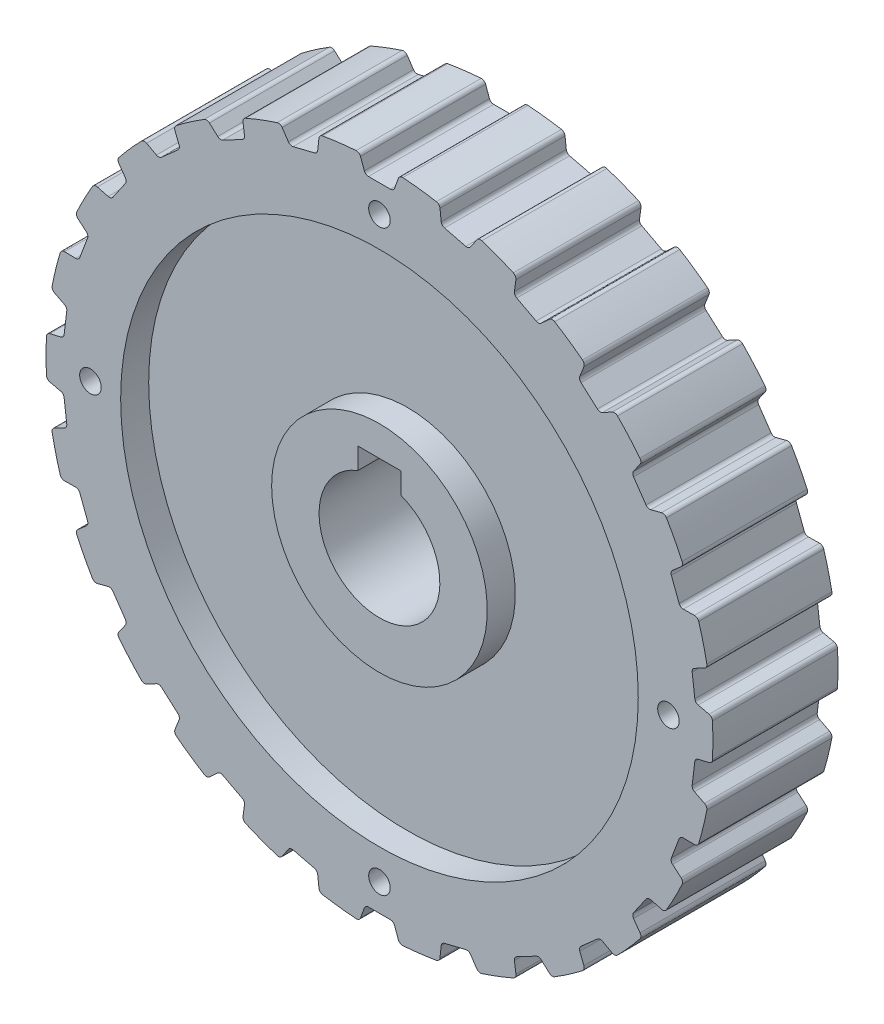
SolidWorks part; units mm, degrees
ref_plane "Front Plane" through (0, 0, 0) normal (0, 0, 1) x (1, 0, 0)
ref_plane "Top Plane" through (0, 0, 0) normal (0, 1, 0) x (1, 0, 0)
ref_plane "Right Plane" through (0, 0, 0) normal (1, 0, 0) x (0, 0, -1)
sketch "Sketch1" plane through (0, 0, 0) normal (0, 1, 0) x (1, 0, 0)
  line L0 (0, 36.1296) -> (0, -19.4741) construction
sketch "Sketch2" plane through (0, 0, 0) normal (0, 1, 0) x (1, 0, 0)
  line L0 (7, 7.25) -> (12.5, 7.25)
  line L1 (12.5, 7.25) -> (12.5, 4)
  line L2 (12.5, 4) -> (30, 4)
  line L3 (30, 4) -> (30, 7.25)
  line L4 (30, 7.25) -> (36, 7.25)
  line L5 (36, 7.25) -> (36, -7.25)
  line L6 (36, -7.25) -> (30, -7.25)
  line L7 (30, -7.25) -> (30, -4)
  line L8 (30, -4) -> (12.5, -4)
  line L9 (12.5, -4) -> (12.5, -7.25)
  line L10 (12.5, -7.25) -> (7, -7.25)
  line L11 (7, -7.25) -> (7, 7.25)
  line L12 (0, 0) -> (7, 0) construction
  line L13 (0, 200036.1296) -> (0, -200019.4741) construction
  dimension "D1" = 36
  dimension "D2" = 30
  dimension "D3" = 12.5
  dimension "D4" = 14.5
  dimension "D5" = 3.25
  dimension "D6" = 7
revolve "Revolve1" add sketch "Sketch2" angle 360 about L0
sketch "Sketch3" plane through (0, 0, 0) normal (0, 0, 1) x (1, 0, 0)
  line L0 (0, 0) -> (0, 9) construction
  line L1 (-2.5, 0) -> (2.5, 0)
  line L2 (-2.5, 0) -> (-2.5, 9)
  line L3 (-2.5, 9) -> (2.5, 9)
  line L4 (2.5, 0) -> (2.5, 9)
  line L5 (0, 9) -> (0, 12.5) construction
  circle A0 centre (0, 0) radius 12.5 construction
  dimension "D1" = 3.5
  dimension "D2" = 5
extrude "Cut-Extrude1" cut sketch "Sketch3" against normal through all both and the other way through all
sketch "Sketch4" plane through (0, 0, 0) normal (0, 0, 1) x (1, 0, 0)
  line L0 (0, 0) -> (0, 30) construction
  line L1 (0, 30) -> (0, 32) construction
  line L2 (0, 32) -> (0, 33.5) construction
  circle A0 centre (0, 0) radius 30 construction
  circle A1 centre (0, 33.5) radius 1.5 construction
  circle A2 centre (33.5, 0) radius 1.5 construction
  circle A3 centre (0, -33.5) radius 1.5 construction
  circle A4 centre (-33.5, 0) radius 1.5 construction
  point P18 (0, 0)
  dimension "D2" = 3
  dimension "D1" = 2
  dimension "D3" = 4
hole_wizard "M3x0.5 Tapped Hole1" positions "Sketch5" profile "Sketch6" tap size "M3x0.5" standard "ANSI Metric" end condition through all
sketch "Sketch5" plane through (0, 0, 7.25) normal (0, 0, 1) x (1, 0, 0)
  point P0 (0, 33.5)
  point P3 (33.5, 0)
  point P6 (-33.5, 0)
  point P9 (0, -33.5)
sketch "Sketch6" plane through (0, 33.5, 7.25) normal (1, 0, 0) x (0, -1, 0)
  line L0 (0, 0) -> (0, 14.5)
  line L1 (0, 14.5) -> (1.25, 14.5)
  line L2 (1.25, 14.5) -> (1.25, 0)
  line L5 (1.25, 0) -> (0, 0)
  line L11 (0, -6.35) -> (0, 107.95) construction
  dimension "Thru Tap Drill Dia." = 2.5
  dimension "Thru Tap Drill Depth" = 14.5
cosmetic thread "Hole Thread1" parameters "D2"=3
cosmetic thread "Hole Thread2" parameters "D2"=3
cosmetic thread "Hole Thread3" parameters "D2"=3
cosmetic thread "Hole Thread4" parameters "D2"=3
sketch "Sketch7" plane through (0, 0, 0) normal (0, 0, 1) x (1, 0, 0)
  line L0 (0, 0) -> (0, 37.6222) construction
  line L1 (-2.325, 38.5772) -> (-2.9401, 40.2672) construction
  line L2 (-2.325, 38.5772) -> (-1.6298, 36.6672) construction
  line L3 (-1.6298, 36.6672) -> (1.6298, 36.6672) construction
  line L4 (1.6298, 36.6672) -> (2.325, 38.5772) construction
  line L5 (2.325, 38.5772) -> (-2.325, 38.5772) construction
  line L6 (0, 36.6672) -> (0, 38.5772) construction
  line L7 (-2.9401, 40.2672) -> (2.9401, 40.2672) construction
  line L8 (2.9401, 40.2672) -> (2.325, 38.5772) construction
  line L9 (0, 38.5772) -> (0, 38.6472) construction
  line L10 (0, 38.6472) -> (0, 40.3744) construction
  line L11 (0, 0) -> (9.0036, 36.529) construction
  line L12 (9.0036, 36.529) -> (9.2489, 37.5242) construction
  line L13 (9.2489, 37.5242) -> (9.6622, 39.2012) construction
  line L14 (0, 39.5108) -> (9.4556, 38.3627) construction
  circle A0 centre (0, 0) radius 36
  circle A1 centre (0, 0) radius 37.6222 construction
  circle A2 centre (-1.2727, 37.1772) radius 0.51 construction
  circle A3 centre (1.2727, 37.1772) radius 0.51 construction
  circle A4 centre (0, 0) radius 38.6472
  circle A5 centre (0, 0) radius 36 construction
  circle A6 centre (0, 0) radius 40.3744 construction
  dimension "D3" = 40
  dimension "D6" = 1.02
  dimension "D1" = 3.6
  dimension "D2" = 9.525
  dimension "D7" = 13.846
  dimension "D4" = 1.91
  dimension "D5" = 4.65
extrude "Boss-Extrude1" add sketch "Sketch7" along normal up to surface and the other way up to surface up to face at (1.25, 33.5, 7.25) other way up to face at (1.25, 33.5, -7.25)
sketch "Sketch8" plane through (0, 0, 0) normal (0, 0, 1) x (1, 0, 0)
  line L6 (-1.6298, 36.6672) -> (-2.3505, 38.6472)
  line L7 (-2.3505, 38.6472) -> (2.3505, 38.6472)
  line L8 (2.3505, 38.6472) -> (1.6298, 36.6672)
  line L9 (1.6298, 36.6672) -> (-1.6298, 36.6672)
  line L10 (-2.325, 38.5772) -> (-1.6298, 36.6672) construction
  line L11 (1.6298, 36.6672) -> (2.325, 38.5772) construction
  line L12 (7.1926, 35.9918) -> (6.9667, 38.0867)
  line L13 (6.9667, 38.0867) -> (11.5311, 36.9617)
  line L14 (11.5311, 36.9617) -> (10.3575, 35.2117)
  line L15 (10.3575, 35.2117) -> (7.1926, 35.9918)
  line L16 (15.597, 33.2246) -> (15.879, 35.3127)
  line L17 (15.879, 35.3127) -> (20.0415, 33.1281)
  line L18 (20.0415, 33.1281) -> (18.4832, 31.7098)
  line L19 (18.4832, 31.7098) -> (15.597, 33.2246)
  line L20 (23.0949, 28.5266) -> (23.8685, 30.4865)
  line L21 (23.8685, 30.4865) -> (27.3872, 27.3692)
  line L22 (27.3872, 27.3692) -> (25.5348, 26.365)
  line L23 (25.5348, 26.365) -> (23.0949, 28.5266)
  line L24 (29.2507, 22.1707) -> (30.4708, 23.8885)
  line L25 (30.4708, 23.8885) -> (33.1412, 20.0197)
  line L26 (33.1412, 20.0197) -> (31.1024, 19.488)
  line L27 (31.1024, 19.488) -> (29.2507, 22.1707)
  line L28 (33.7065, 14.5263) -> (35.3023, 15.9022)
  line L29 (35.3023, 15.9022) -> (36.9692, 11.5068)
  line L30 (36.9692, 11.5068) -> (34.8624, 11.4785)
  line L31 (34.8624, 11.4785) -> (33.7065, 14.5263)
  line L32 (36.2034, 6.0377) -> (38.0821, 6.9917)
  line L33 (38.0821, 6.9917) -> (38.6487, 2.3251)
  line L34 (38.6487, 2.3251) -> (36.5963, 2.8018)
  line L35 (36.5963, 2.8018) -> (36.2034, 6.0377)
  line L36 (36.5963, -2.8018) -> (38.6487, -2.3251)
  line L37 (38.6487, -2.3251) -> (38.0821, -6.9917)
  line L38 (38.0821, -6.9917) -> (36.2034, -6.0377)
  line L39 (36.2034, -6.0377) -> (36.5963, -2.8018)
  line L40 (34.8624, -11.4785) -> (36.9692, -11.5068)
  line L41 (36.9692, -11.5068) -> (35.3023, -15.9022)
  line L42 (35.3023, -15.9022) -> (33.7065, -14.5263)
  line L43 (33.7065, -14.5263) -> (34.8624, -11.4785)
  line L44 (31.1024, -19.488) -> (33.1412, -20.0197)
  line L45 (33.1412, -20.0197) -> (30.4708, -23.8885)
  line L46 (30.4708, -23.8885) -> (29.2507, -22.1707)
  line L47 (29.2507, -22.1707) -> (31.1024, -19.488)
  line L48 (25.5348, -26.365) -> (27.3872, -27.3692)
  line L49 (27.3872, -27.3692) -> (23.8685, -30.4865)
  line L50 (23.8685, -30.4865) -> (23.0949, -28.5266)
  line L51 (23.0949, -28.5266) -> (25.5348, -26.365)
  line L52 (18.4832, -31.7098) -> (20.0415, -33.1281)
  line L53 (20.0415, -33.1281) -> (15.879, -35.3127)
  line L54 (15.879, -35.3127) -> (15.597, -33.2246)
  line L55 (15.597, -33.2246) -> (18.4832, -31.7098)
  line L56 (10.3575, -35.2117) -> (11.5311, -36.9617)
  line L57 (11.5311, -36.9617) -> (6.9667, -38.0867)
  line L58 (6.9667, -38.0867) -> (7.1926, -35.9918)
  line L59 (7.1926, -35.9918) -> (10.3575, -35.2117)
  line L60 (1.6298, -36.6672) -> (2.3505, -38.6472)
  line L61 (2.3505, -38.6472) -> (-2.3505, -38.6472)
  line L62 (-2.3505, -38.6472) -> (-1.6298, -36.6672)
  line L63 (-1.6298, -36.6672) -> (1.6298, -36.6672)
  line L64 (-7.1926, -35.9918) -> (-6.9667, -38.0867)
  line L65 (-6.9667, -38.0867) -> (-11.5311, -36.9617)
  line L66 (-11.5311, -36.9617) -> (-10.3575, -35.2117)
  line L67 (-10.3575, -35.2117) -> (-7.1926, -35.9918)
  line L68 (-15.597, -33.2246) -> (-15.879, -35.3127)
  line L69 (-15.879, -35.3127) -> (-20.0415, -33.1281)
  line L70 (-20.0415, -33.1281) -> (-18.4832, -31.7098)
  line L71 (-18.4832, -31.7098) -> (-15.597, -33.2246)
  line L72 (-23.0949, -28.5266) -> (-23.8685, -30.4865)
  line L73 (-23.8685, -30.4865) -> (-27.3872, -27.3692)
  line L74 (-27.3872, -27.3692) -> (-25.5348, -26.365)
  line L75 (-25.5348, -26.365) -> (-23.0949, -28.5266)
  line L76 (-29.2507, -22.1707) -> (-30.4708, -23.8885)
  line L77 (-30.4708, -23.8885) -> (-33.1412, -20.0197)
  line L78 (-33.1412, -20.0197) -> (-31.1024, -19.488)
  line L79 (-31.1024, -19.488) -> (-29.2507, -22.1707)
  line L80 (-33.7065, -14.5263) -> (-35.3023, -15.9022)
  line L81 (-35.3023, -15.9022) -> (-36.9692, -11.5068)
  line L82 (-36.9692, -11.5068) -> (-34.8624, -11.4785)
  line L83 (-34.8624, -11.4785) -> (-33.7065, -14.5263)
  line L84 (-36.2034, -6.0377) -> (-38.0821, -6.9917)
  line L85 (-38.0821, -6.9917) -> (-38.6487, -2.3251)
  line L86 (-38.6487, -2.3251) -> (-36.5963, -2.8018)
  line L87 (-36.5963, -2.8018) -> (-36.2034, -6.0377)
  line L88 (-36.5963, 2.8018) -> (-38.6487, 2.3251)
  line L89 (-38.6487, 2.3251) -> (-38.0821, 6.9917)
  line L90 (-38.0821, 6.9917) -> (-36.2034, 6.0377)
  line L91 (-36.2034, 6.0377) -> (-36.5963, 2.8018)
  line L92 (-34.8624, 11.4785) -> (-36.9692, 11.5068)
  line L93 (-36.9692, 11.5068) -> (-35.3023, 15.9022)
  line L94 (-35.3023, 15.9022) -> (-33.7065, 14.5263)
  line L95 (-33.7065, 14.5263) -> (-34.8624, 11.4785)
  line L96 (-31.1024, 19.488) -> (-33.1412, 20.0197)
  line L97 (-33.1412, 20.0197) -> (-30.4708, 23.8885)
  line L98 (-30.4708, 23.8885) -> (-29.2507, 22.1707)
  line L99 (-29.2507, 22.1707) -> (-31.1024, 19.488)
  line L100 (-25.5348, 26.365) -> (-27.3872, 27.3692)
  line L101 (-27.3872, 27.3692) -> (-23.8685, 30.4865)
  line L102 (-23.8685, 30.4865) -> (-23.0949, 28.5266)
  line L103 (-23.0949, 28.5266) -> (-25.5348, 26.365)
  line L104 (-18.4832, 31.7098) -> (-20.0415, 33.1281)
  line L105 (-20.0415, 33.1281) -> (-15.879, 35.3127)
  line L106 (-15.879, 35.3127) -> (-15.597, 33.2246)
  line L107 (-15.597, 33.2246) -> (-18.4832, 31.7098)
  line L108 (-10.3575, 35.2117) -> (-11.5311, 36.9617)
  line L109 (-11.5311, 36.9617) -> (-6.9667, 38.0867)
  line L110 (-6.9667, 38.0867) -> (-7.1926, 35.9918)
  line L111 (-7.1926, 35.9918) -> (-10.3575, 35.2117)
  circle A0 centre (0, 0) radius 38.6472 construction
  point P119 (0, 0)
  dimension "D1" = 26
extrude "Cut-Extrude2" cut sketch "Sketch8" against normal through all both and the other way through all
fillet "Fillet2" radius 0.51 104 edges at (-6.9747, 38.0126, 0) (-11.4896, 36.8998, 0) (-15.869, 35.2389, 0) (-19.9864, 33.0779, 0) (-23.8411, 30.4172, 0) (-27.3217, 27.3337, 0) (-30.4277, 23.8278, 0) (-33.0692, 20.0009, 0) (-35.2459, 15.8536, 0) (-36.8948, 11.5058, 0) (-38.0157, 6.958, 0) (-38.5762, 2.3419, 0) (-38.5762, -2.3419, 0) (-38.0157, -6.958, 0) (-36.8948, -11.5058, 0) (-35.2459, -15.8536, 0) (-33.0692, -20.0009, 0) (-30.4277, -23.8278, 0) (-27.3217, -27.3337, 0) (-23.8411, -30.4172, 0) (-19.9864, -33.0779, 0) (-15.869, -35.2389, 0) (-11.4896, -36.8998, 0) (-6.9747, -38.0126, 0) (-2.325, -38.5772, 0) (2.325, -38.5772, 0) (6.9747, -38.0126, 0) (11.4896, -36.8998, 0) (15.869, -35.2389, 0) (19.9864, -33.0779, 0) (23.8411, -30.4172, 0) (27.3217, -27.3337, 0) (30.4277, -23.8278, 0) (33.0692, -20.0009, 0) (35.2459, -15.8536, 0) (36.8948, -11.5058, 0) (38.0157, -6.958, 0) (38.5762, -2.3419, 0) (38.5762, 2.3419, 0) (38.0157, 6.958, 0) (36.8948, 11.5058, 0) (35.2459, 15.8536, 0) (33.0692, 20.0009, 0) (30.4277, 23.8278, 0) (27.3217, 27.3337, 0) (23.8411, 30.4172, 0) (19.9864, 33.0779, 0) (15.869, 35.2389, 0) (11.4896, 36.8998, 0) (6.9747, 38.0126, 0) (2.325, 38.5772, 0) (-7.1926, 35.9918, 0) (-10.3575, 35.2117, 0) (-15.597, 33.2246, 0) (-18.4832, 31.7098, 0) (-23.0949, 28.5266, 0) (-25.5348, 26.365, 0) (-29.2507, 22.1707, 0) (-31.1024, 19.488, 0) (-33.7065, 14.5263, 0) (-34.8624, 11.4785, 0) (-36.2034, 6.0377, 0) (-36.5963, 2.8018, 0) (-36.5963, -2.8018, 0) (-36.2034, -6.0377, 0) (-34.8624, -11.4785, 0) (-33.7065, -14.5263, 0) (-31.1024, -19.488, 0) (-29.2507, -22.1707, 0) (-25.5348, -26.365, 0) (-23.0949, -28.5266, 0) (-18.4832, -31.7098, 0) (-15.597, -33.2246, 0) (-10.3575, -35.2117, 0) (-7.1926, -35.9918, 0) (-1.6298, -36.6672, 0) (1.6298, -36.6672, 0) (7.1926, -35.9918, 0) (10.3575, -35.2117, 0) (15.597, -33.2246, 0) (18.4832, -31.7098, 0) (23.0949, -28.5266, 0) (25.5348, -26.365, 0) (29.2507, -22.1707, 0) (31.1024, -19.488, 0) (33.7065, -14.5263, 0) (34.8624, -11.4785, 0) (36.2034, -6.0377, 0) (36.5963, -2.8018, 0) (36.5963, 2.8018, 0) (36.2034, 6.0377, 0) (34.8624, 11.4785, 0) (33.7065, 14.5263, 0) (31.1024, 19.488, 0) (29.2507, 22.1707, 0) (25.5348, 26.365, 0) (23.0949, 28.5266, 0) (18.4832, 31.7098, 0) (15.597, 33.2246, 0) (10.3575, 35.2117, 0) (7.1926, 35.9918, 0) (1.6298, 36.6672, 0) (-1.6298, 36.6672, 0) (-2.325, 38.5772, 0)
